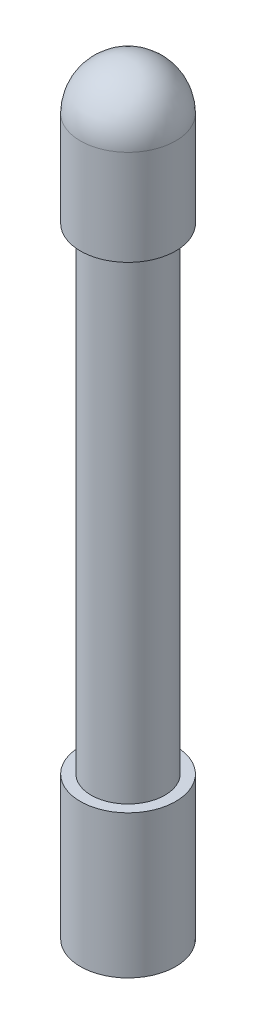
SolidWorks part; units mm, degrees
ref_plane "Front Plane" through (0, 0, 0) normal (0, 0, 1) x (1, 0, 0)
ref_plane "Top Plane" through (0, 0, 0) normal (0, 1, 0) x (1, 0, 0)
ref_plane "Right Plane" through (0, 0, 0) normal (1, 0, 0) x (0, 0, -1)
sketch "Sketch1" plane through (0, 0, 0) normal (0, 1, 0) x (1, 0, 0)
  circle A0 centre (0, 0) radius 2.54
  dimension "D1" = 5.08
extrude "Boss-Extrude1" add sketch "Sketch1" along normal blind 7.62
sketch "Sketch2" plane through (0, 7.62, 0) normal (0, 1, 0) x (1, 0, 0)
  circle A0 centre (0, 0) radius 1.965
  dimension "D1" = 3.9301
extrude "Boss-Extrude2" add sketch "Sketch2" along normal blind 25.4
sketch "Sketch3" plane through (0, 33.02, 0) normal (0, 1, 0) x (1, 0, 0)
  circle A0 centre (0, 0) radius 2.54
  dimension "D1" = 5.08
extrude "Boss-Extrude3" add sketch "Sketch3" along normal blind 7.62
fillet "Fillet1" radius 2.54 1 edges at (0, 40.64, 2.54)
